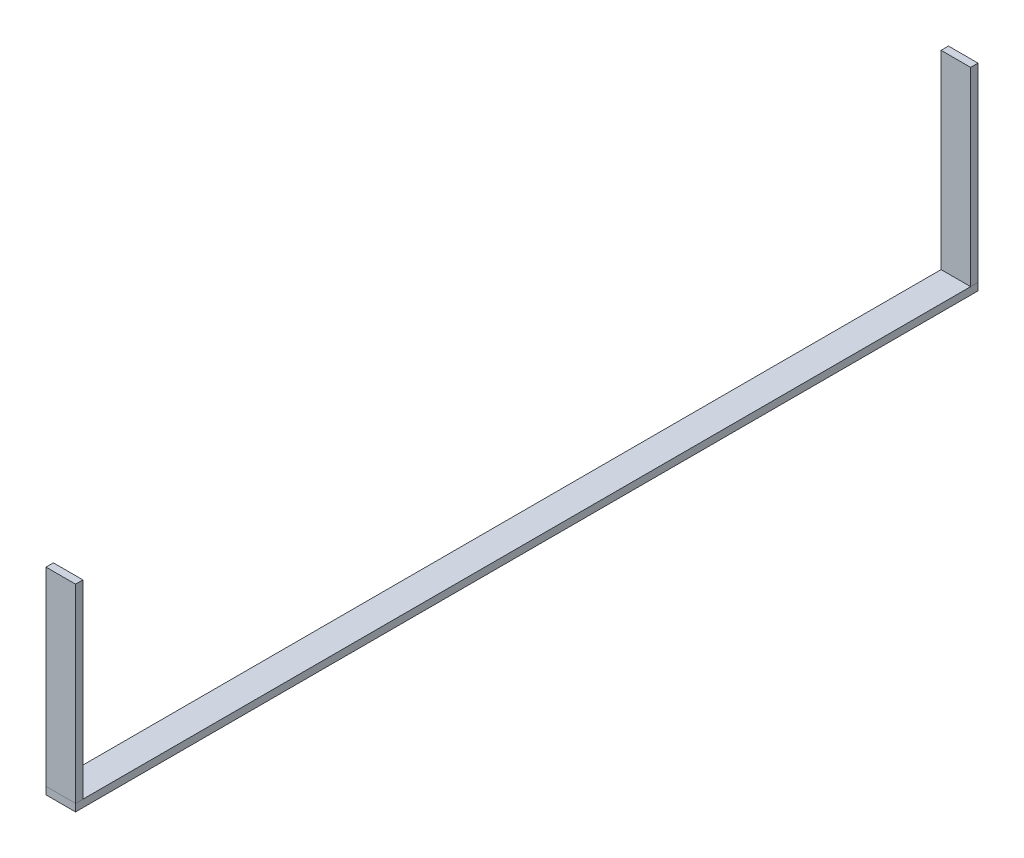
SolidWorks part; units mm, degrees
ref_plane "Front Plane" through (0, 0, 0) normal (0, 0, 1) x (1, 0, 0)
ref_plane "Top Plane" through (0, 0, 0) normal (0, 1, 0) x (1, 0, 0)
ref_plane "Right Plane" through (0, 0, 0) normal (1, 0, 0) x (0, 0, -1)
sketch "Sketch1" plane through (0, 0, 0) normal (0, 1, 0) x (1, 0, 0)
  line L1 (-6.35, 194) -> (6.35, 194)
  line L2 (-6.35, 194) -> (-6.35, -194)
  line L3 (-6.35, -194) -> (6.35, -194)
  line L4 (6.35, 194) -> (6.35, -194)
  line L5 (-6.35, 194) -> (6.35, -194) construction
  line L6 (-6.35, -194) -> (6.35, 194) construction
  point P0 (0, 0)
  dimension "D1" = 12.7
  dimension "D2" = 388
extrude "Boss-Extrude1" add sketch "Sketch1" along normal blind 3.175 contours L4 L3 L2 L1
sketch "Sketch2" plane through (0, 3.175, 0) normal (0, 1, 0) x (1, 0, 0)
  line L0 (-6.35, 194) -> (-6.35, -194) construction
  line L1 (6.35, -194) -> (-6.35, -194)
  line L2 (6.35, -194) -> (6.35, -190.825)
  line L3 (6.35, -190.825) -> (-6.35, -190.825)
  line L4 (-6.35, -194) -> (-6.35, -190.825)
  line L5 (6.35, 194) -> (6.35, -194) construction
  line L7 (-6.35, 194) -> (6.35, 194)
  line L8 (-6.35, 194) -> (-6.35, 190.825)
  line L9 (-6.35, 190.825) -> (6.35, 190.825)
  line L10 (6.35, 194) -> (6.35, 190.825)
  dimension "D1" = 3.175
  dimension "D2" = 3.175
extrude "Boss-Extrude2" add sketch "Sketch2" along normal blind 81.65 separate body
equation "\"Battery_Case_Width\"= 40cm"
equation "\"Battery_Case_Length\"= 25cm"
equation "\"Battery_Case_Thickness\" = 6mm"
equation "\"Battery_Case_Height\"= 10cm"
equation "\"D2@Sketch1\"=\"Battery_Case_Width\"-2*\"Battery_Case_Thickness\""
